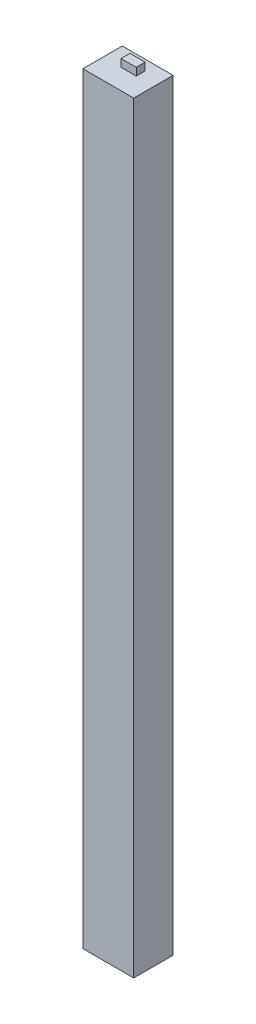
SolidWorks part; units mm, degrees
ref_plane "前视基准面" through (0, 0, 0) normal (0, 0, 1) x (1, 0, 0)
ref_plane "上视基准面" through (0, 0, 0) normal (0, 1, 0) x (1, 0, 0)
ref_plane "右视基准面" through (0, 0, 0) normal (1, 0, 0) x (0, 0, -1)
sketch "草图1" plane through (0, 0, 0) normal (0, 0, 1) x (1, 0, 0)
  line L1 (-10, 150) -> (10, 150)
  line L2 (-10, 150) -> (-10, -150)
  line L3 (-10, -150) -> (10, -150)
  line L4 (10, 150) -> (10, -150)
  line L5 (-10, 150) -> (10, -150) construction
  line L6 (-10, -150) -> (10, 150) construction
  point P0 (0, 0)
  dimension "D1" = 300
  dimension "D2" = 20
extrude "主体" add sketch "草图1" along normal blind 15.5
sketch "草图2" plane through (0, 150, 0) normal (0, 1, 0) x (1, 0, 0)
  line L0 (0, -8.525) -> (0, 8.525) construction
  line L1 (-3, -4) -> (3, -4)
  line L2 (-3, -4) -> (-3, -7.5)
  line L3 (-3, -7.5) -> (3, -7.5)
  line L4 (3, -4) -> (3, -7.5)
  line L5 (-3, -4) -> (3, -7.5) construction
  line L6 (-3, -7.5) -> (3, -4) construction
  line L9 (10, -15.5) -> (-10, -15.5) construction
  line L10 (10, 0) -> (-10, 0) construction
  point P0 (0, -5.75)
  point P5 (0, 0)
  dimension "D1" = 6
  dimension "D2" = 8
  dimension "D3" = 4
extrude "导线" add sketch "草图2" along normal blind 3
